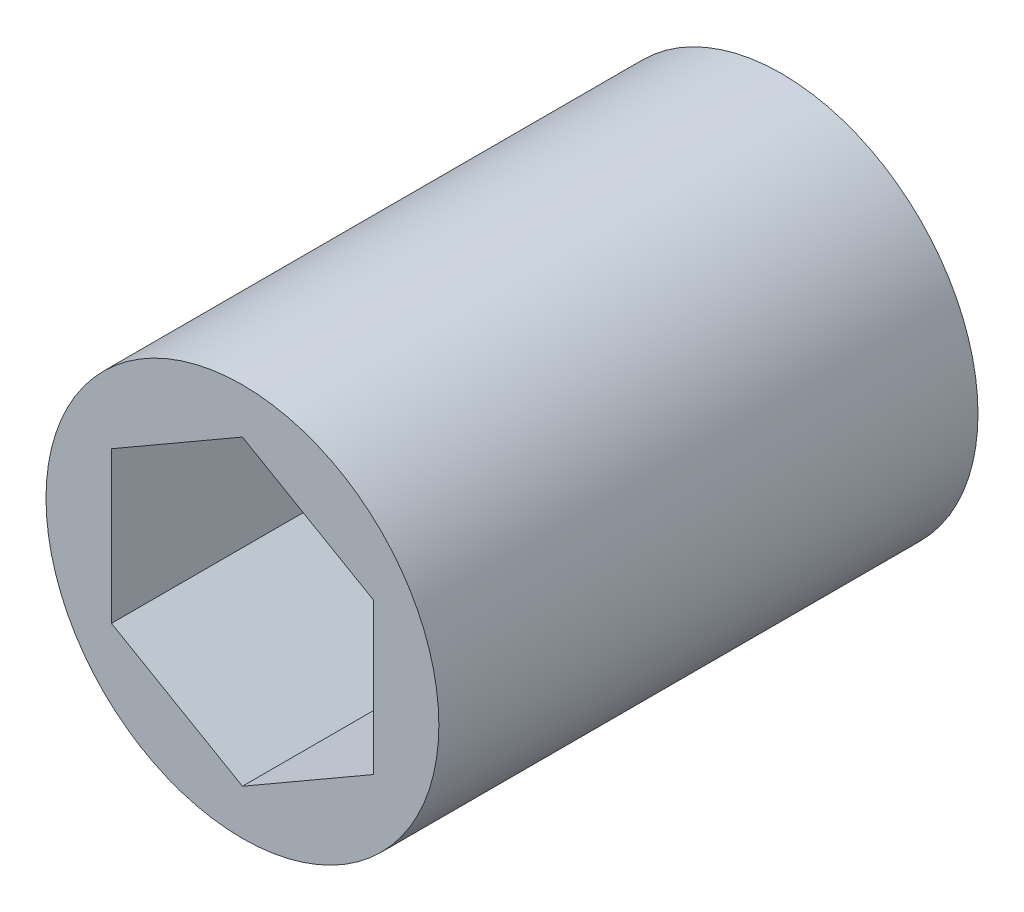
SolidWorks part; units mm, degrees
ref_plane "Front Plane" through (0, 0, 0) normal (0, 0, 1) x (1, 0, 0)
ref_plane "Top Plane" through (0, 0, 0) normal (0, 1, 0) x (1, 0, 0)
ref_plane "Right Plane" through (0, 0, 0) normal (1, 0, 0) x (0, 0, -1)
sketch "Sketch1" plane through (0, 0, 0) normal (0, 0, 1) x (1, 0, 0)
  line L1 (0, 7.3323) -> (-6.35, 3.6662)
  line L2 (-6.35, 3.6662) -> (-6.35, -3.6662)
  line L3 (-6.35, -3.6662) -> (0, -7.3323)
  line L4 (0, -7.3323) -> (6.35, -3.6662)
  line L5 (6.35, -3.6662) -> (6.35, 3.6662)
  line L6 (6.35, 3.6662) -> (0, 7.3323)
  circle A0 centre (0, 0) radius 9.525
  circle A1 centre (0, 0) radius 6.35 construction
  dimension "D1" = 19.05
  dimension "D2" = 12.7
extrude "Boss-Extrude1" add sketch "Sketch1" along normal mid plane 26.1445
